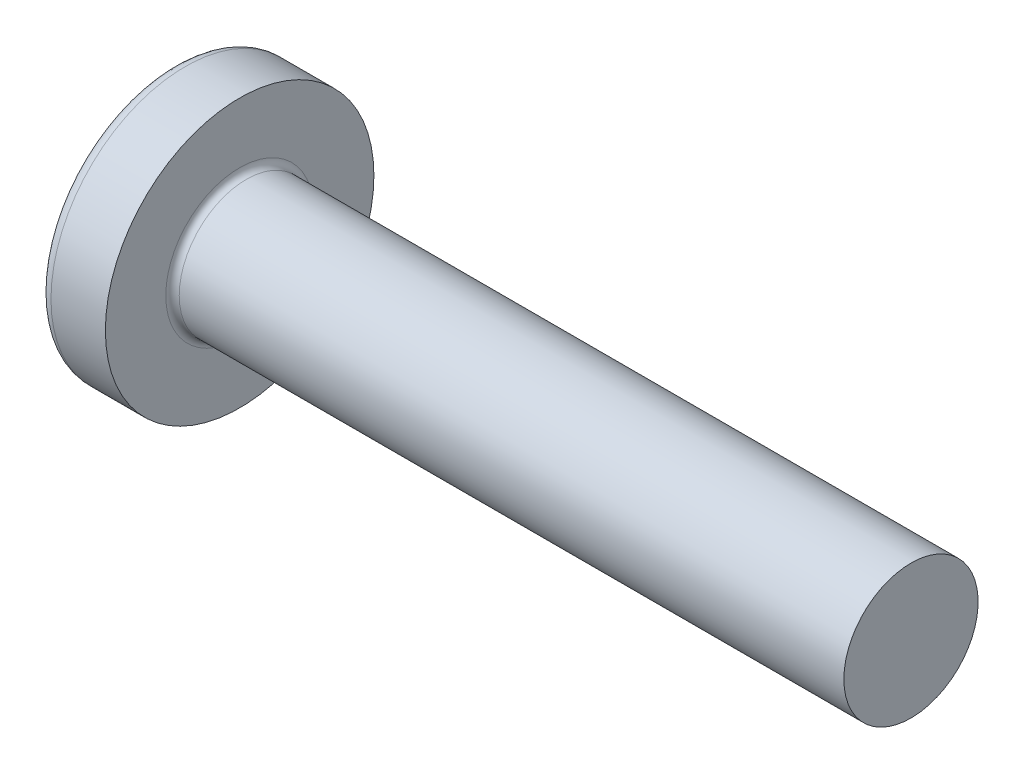
SolidWorks part; units mm, degrees
ref_plane "Plane1" through (0, 0, 0) normal (0, 0, 1) x (1, 0, 0)
ref_plane "Plane2" through (0, 0, 0) normal (0, 1, 0) x (1, 0, 0)
ref_plane "Plane3" through (0, 0, 0) normal (1, 0, 0) x (0, 0, -1)
sketch "BodySke" plane through (0, 0, 0) normal (0, 0, 1) x (1, 0, 0)
  line L0 (1.6, 1) -> (1.6, 2)
  line L1 (1.8, 6.35) -> (1.8, -3.175) construction
  line L2 (-25.4, 0) -> (127, 0) construction
  line L3 (11.6, 0) -> (0, 0)
  line L4 (1.6, 1) -> (11.6, 1)
  line L5 (11.6, 1) -> (11.6, 0)
  line L6 (0.79, 2) -> (1.6, 2)
  line L8 (1.6, 6.35) -> (1.6, -3.175) construction
  arc A0 (0.6464, 1.9285) -> (0, 0) centre (3.2, 0) ccw
  arc A2 (0.6464, 1.9285) -> (0.79, 2) centre (0.79, 1.82) cw
  dimension "Head_fillet_rad" = 0.18
  dimension "Head_crown_rad" = 3.2
  dimension "Head_ht" = 1.6
  dimension "Diameter" = 2
  dimension "Length" = 10
  dimension "Head_dia" = 4
  dimension "Advance" = 0.4
  dimension "Thread_nom" = 10
revolve "Base-Revolve" add sketch "BodySke"
cosmetic thread "ThreadCosmetic" [suppressed]
fillet "Fillet1" radius 0.1 1 edges at (1.6, 0, 1)
sketch "Sketch3" plane through (0, 0, 0) normal (1, 0, 0) x (0, 0, -1)
  line L0 (0.24, -1.05) -> (-0.24, -1.05)
  line L1 (0.24, -1.05) -> (0.24, 1.05)
  line L2 (-0.24, 1.05) -> (0.24, 1.05)
  line L3 (-0.24, 1.05) -> (-0.24, -1.05)
  dimension "D1" = 1.05
  dimension "Cross_dia" = 2.1
  dimension "D2" = 0.24
  dimension "Cross_width" = 0.48
ref_plane "Plane4" through (1.42, 0, 0) normal (1, 0, 0) x (0, 0, -1)
sketch "Sketch4" plane through (1.42, 0, 0) normal (1, 0, 0) x (0, 0, -1)
  line L0 (0.24, -0.342) -> (-0.24, -0.342)
  line L1 (0.24, -0.342) -> (0.24, 0.342)
  line L2 (-0.24, 0.342) -> (0.24, 0.342)
  line L3 (-0.24, 0.342) -> (-0.24, -0.342)
  dimension "D1" = 0.48
  dimension "D2" = 0.684
  dimension "D3" = 0.24
  dimension "D4" = 0.342
loft "Recess" cut profiles "Sketch3", "Sketch4"
pattern_circular "RecPat" count 2 every 90 about axis through (0, 0, 0) along (1, 0, 0) of "Recess"
sketch "RecCorSke" plane through (0, 0, 0) normal (0, 0, 1) x (1, 0, 0)
  line L0 (-3.175, 0) -> (15.875, 0) construction
  line L1 (-25.4, 0) -> (127, 0) construction
  line L2 (0, 0) -> (0, 0.4548)
  line L3 (0, 0.4548) -> (1.42, 0.3555)
  line L4 (1.42, 0.3555) -> (1.5355, 0)
  line L5 (1.5355, 0) -> (0, 0)
  dimension "Diameter" = 0.711
  dimension "Depth" = 1.42
  dimension "Draft_angle" = 4
  dimension "Bottom_angle" = 18
revolve "RecessCore" cut sketch "RecCorSke" angle 360 about L0
sketch "ThdSchSke" plane through (0, 0, 0) normal (0, 0, 1) x (1, 0, 0)
  line L0 (2.4, -0.774) -> (2.2418, -1)
  line L1 (2.4, -0.774) -> (2.5582, -1)
  line L2 (2.5582, -1) -> (2.5582, -1.25)
  line L3 (-3.175, 0) -> (5.1513, 0) construction
  line L5 (2.5582, -1.25) -> (2.2418, -1.25)
  line L6 (2.2418, -1.25) -> (2.2418, -1)
  dimension "Thread_minor" = 1.548
  dimension "Diameter" = 2
  dimension "Start" = 2.4
  dimension "SideAngle" = 55
  dimension "VeeAngle" = 70
  dimension "Overcut" = 2.5
revolve "ThreadSchematic" [suppressed] cut sketch "ThdSchSke" angle 360 about L3
pattern_linear "ThdSchPat" [suppressed]
equation "\"D1@Sketch3\" = \"Cross_dia@Sketch3\" / 2"
equation "\"D2@Sketch3\" = \"Cross_width@Sketch3\" / 2"
equation "\"Depth@RecCorSke\" = \"Cross_depth@Plane4\""
equation "\"D1@Sketch4\" = \"Cross_width@Sketch3\""
equation "\"D2@Sketch4\" = \"Cross_dia@Sketch3\" - 2.0 * \"Cross_depth@Plane4\" * tan(26.5  * 0.017453292)"
equation "\"D3@Sketch4\" = \"D1@Sketch4\" / 2"
equation "\"D4@Sketch4\" = \"D2@Sketch4\" / 2"
equation "\"Thread_length@ThreadCosmetic\" = ((sgn( (\"Length@BodySke\" - \"Advance@BodySke\" * 2.0 ) - \"Thread_nom@BodySke\" )-1)*( (\"Length@BodySke\" - \"Advance@BodySke\" * 2.0 ) - \"Thread_nom@BodySke\" ))/-2+ \"Thread_nom@BodySke\""
equation "\"Thread_minor@ThdSchSke\" = \"Thread_minor@ThreadCosmetic\""
equation "\"Diameter@ThdSchSke\" = \"Diameter@BodySke\""
equation "\"Overcut@ThdSchSke\" = \"Diameter@BodySke\" * 1.25"
equation "\"Start@ThdSchSke\" = \"Head_ht@BodySke\" + \"Length@BodySke\" - \"Thread_length@ThreadCosmetic\"  '---Non-countersunk---"
equation "\"Num_threads@ThdSchPat\" = int( \"Thread_length@ThreadCosmetic\" / \"Advance@BodySke\" + 0.999 )  + 1"
equation "\"Advance@ThdSchPat\" = \"Thread_length@ThreadCosmetic\" /  (\"Num_threads@ThdSchPat\" - 1) 'relax it"
